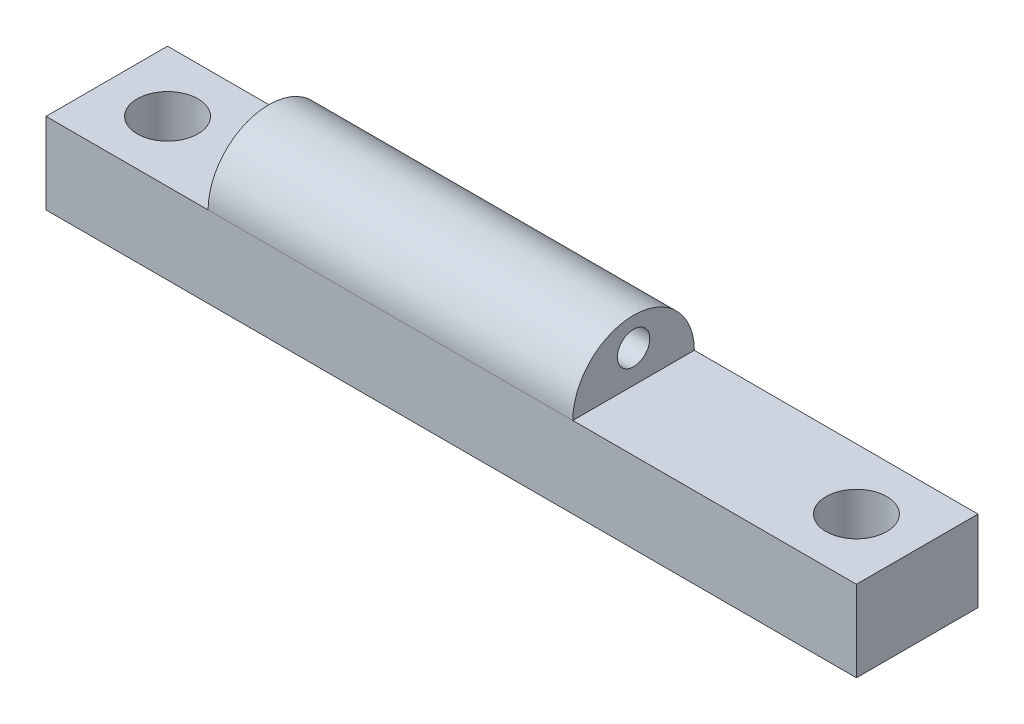
SolidWorks part; units mm, degrees
ref_plane "Front Plane" through (0, 0, 0) normal (0, 0, 1) x (1, 0, 0)
ref_plane "Top Plane" through (0, 0, 0) normal (0, 1, 0) x (1, 0, 0)
ref_plane "Right Plane" through (0, 0, 0) normal (1, 0, 0) x (0, 0, -1)
sketch "Sketch1" plane through (0, 0, 0) normal (0, 1, 0) x (1, 0, 0)
  line L1 (-25.4, 3.81) -> (25.4, 3.81)
  line L2 (-25.4, 3.81) -> (-25.4, -3.81)
  line L3 (-25.4, -3.81) -> (25.4, -3.81)
  line L4 (25.4, 3.81) -> (25.4, -3.81)
  line L5 (-25.4, 3.81) -> (25.4, -3.81) construction
  line L6 (-25.4, -3.81) -> (25.4, 3.81) construction
  point P0 (0, 0)
  dimension "D1" = 50.8
  dimension "D2" = 7.62
extrude "Boss-Extrude1" add sketch "Sketch1" along normal blind 5.08
sketch "Sketch2" plane through (25.4, 0, 0) normal (1, 0, 0) x (0, 0, -1)
  line L0 (-3.81, 5.08) -> (3.81, 5.08) construction
  line L5 (-3.81, 0) -> (3.81, 0)
  line L6 (3.81, 0) -> (3.81, 5.08)
  line L7 (3.81, 5.08) -> (-3.81, 5.08)
  line L8 (-3.81, 5.08) -> (-3.81, 0)
  line L11 (3.81, 5.08) -> (-3.81, 5.08)
  arc A0 (-3.81, 5.08) -> (3.81, 5.08) centre (0, 5.08) cw
  circle A1 centre (0, 7.112) radius 1.016
  point P3 (0, 0)
  dimension "D3" = 2.032
  dimension "D2" = 2.032
  dimension "D1" = 0
extrude "Boss-Extrude2" add sketch "Sketch2" against normal blind 22.86 from offset 17.78 offset against normal yes
sketch "Sketch3" plane through (0, 5.08, 0) normal (0, 1, 0) x (1, 0, 0)
  line L0 (-25.4, 3.81) -> (-25.4, -3.81) construction
  line L1 (25.4, -3.81) -> (25.4, 3.81) construction
  circle A0 centre (-21.59, 0) radius 1.905
  circle A1 centre (21.59, 0) radius 1.905
  point P8 (0, 0)
  point P10 (0, 0)
  dimension "D1" = 3.81
  dimension "D2" = 3.81
  dimension "D3" = 3.81
extrude "Cut-Extrude1" cut sketch "Sketch3" against normal through all
